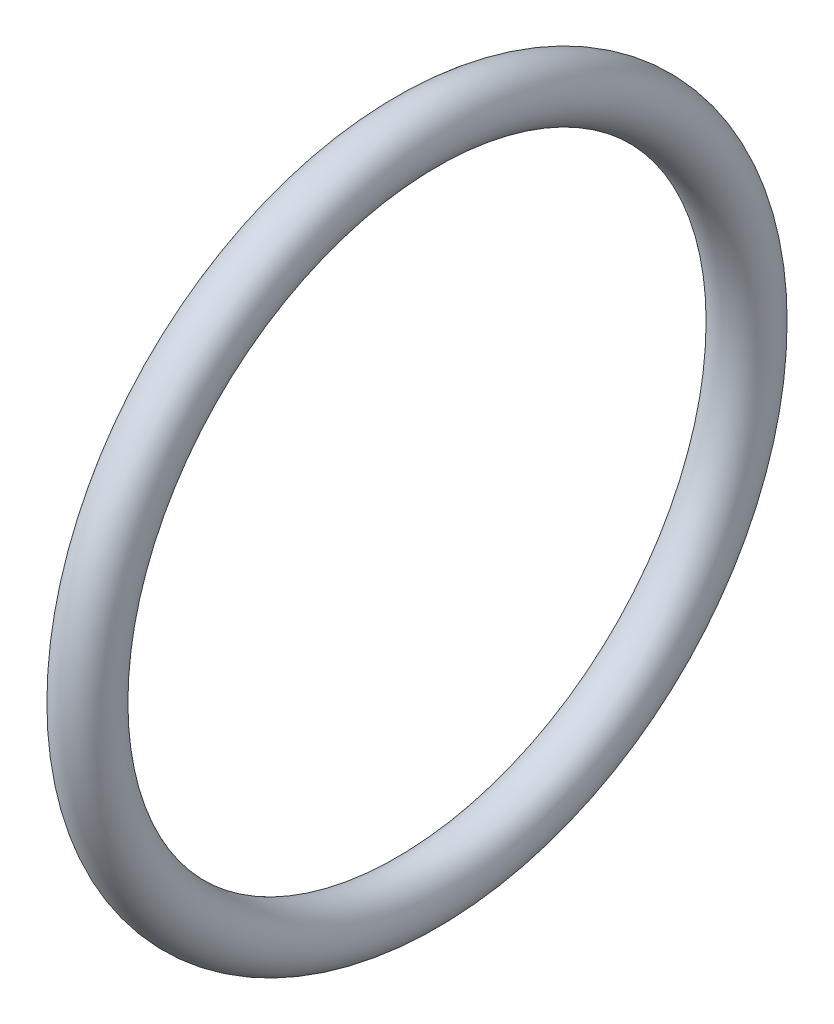
SolidWorks part; units mm, degrees
ref_plane "Plan de face" through (0, 0, 0) normal (0, 0, 1) x (1, 0, 0)
ref_plane "Plan de dessus" through (0, 0, 0) normal (0, 1, 0) x (1, 0, 0)
ref_plane "Plan de droite" through (0, 0, 0) normal (1, 0, 0) x (0, 0, -1)
sketch "Esquisse1" plane through (0, 0, 0) normal (0, 0, 1) x (1, 0, 0)
  line L0 (-4.852, -23) -> (7.7441, -23) construction
  circle A0 centre (0, 0) radius 2
  dimension "D1" = 4
  dimension "D2" = 23
revolve "Révolution1" add sketch "Esquisse1" angle 360 about L0
